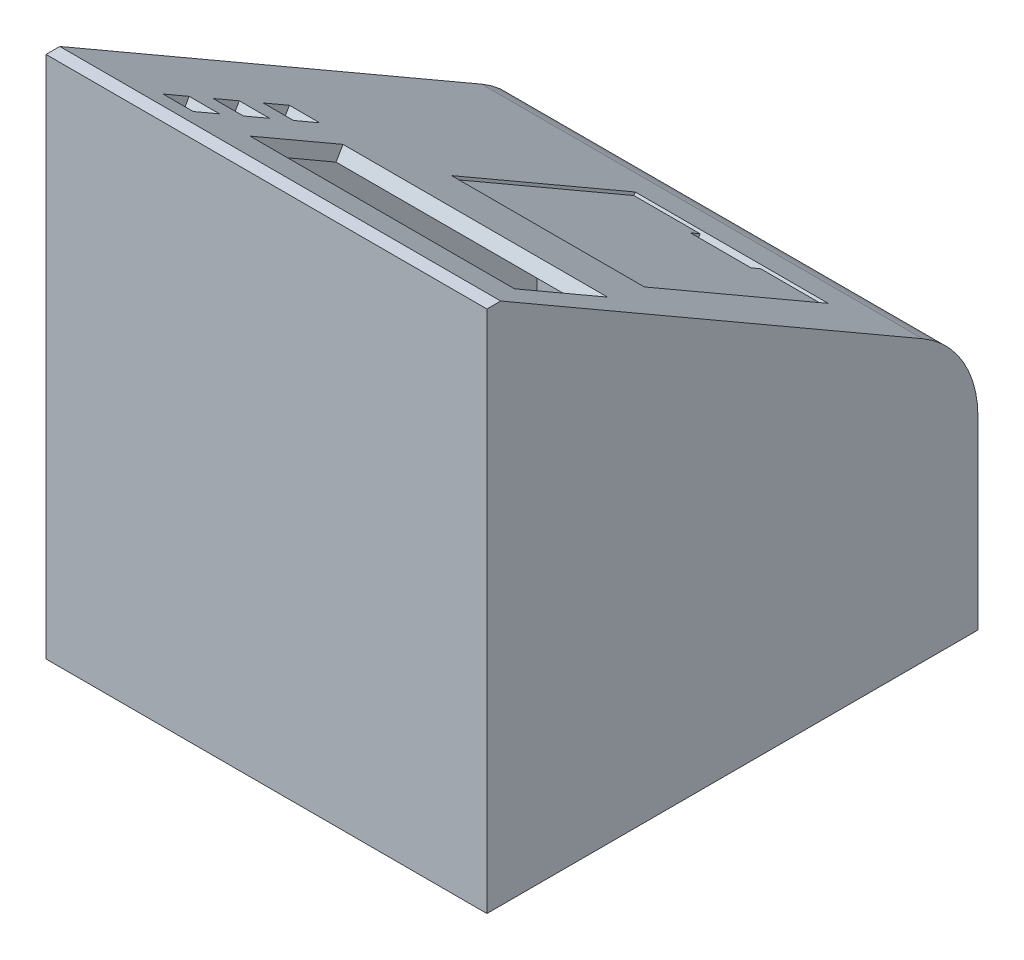
SolidWorks part; units mm, degrees
ref_plane "Front Plane" through (0, 0, 0) normal (0, 0, 1) x (1, 0, 0)
ref_plane "Top Plane" through (0, 0, 0) normal (0, 1, 0) x (1, 0, 0)
ref_plane "Right Plane" through (0, 0, 0) normal (1, 0, 0) x (0, 0, -1)
sketch "Sketch1" plane through (0, 0, 0) normal (1, 0, 0) x (0, 0, -1)
  line L0 (0, 0) -> (173.2051, -100)
  line L1 (173.2051, -100) -> (173.2051, -190)
  line L2 (173.2051, -190) -> (0, -190)
  line L3 (0, -190) -> (0, 0)
  line L4 (173.2051, -100) -> (290.6561, -100) construction
  dimension "D1" = 90
  dimension "D2" = 200
  dimension "D3" = 150
extrude "Boss-Extrude1" add sketch "Sketch1" along normal blind 5
ref_plane "Plane1" through (0, 0, 0) normal (0, 0.866, -0.5) x (1, 0, 0)
sketch "Sketch2" plane through (0, 0, 0) normal (0, 0.866, -0.5) x (1, 0, 0)
  line L0 (0, 200) -> (160, 200)
  line L1 (0, 200) -> (0, 0) construction
  line L2 (5, 200) -> (0, 200) construction
  line L3 (0, 200) -> (0, 0)
  line L4 (0, 0) -> (160, 0)
  line L5 (160, 0) -> (160, 200)
  dimension "D1" = 160
  dimension "D2" = 160
extrude "Boss-Extrude2" add sketch "Sketch2" against normal blind 5 contours L4 L5 L0 L3
ref_plane "Plane3" through (0, 0, 0) normal (0, 0, 1) x (1, 0, 0)
sketch "Sketch4" plane through (0, 0, 0) normal (0, 0, 1) x (1, 0, 0)
  line L0 (0, 0) -> (160, 0)
  line L1 (160, 0) -> (160, -190)
  line L2 (0, 0) -> (0, -190)
  line L3 (5, -190) -> (0, -190) construction
  line L4 (0, -190) -> (160, -190)
extrude "Boss-Extrude4" add sketch "Sketch4" along normal blind 5
ref_plane "Plane4" through (0, 0, -173.2051) normal (0, 0, -1) x (-1, 0, 0)
sketch "Sketch5" plane through (0, 0, -173.2051) normal (0, 0, -1) x (-1, 0, 0)
  line L0 (0, -100) -> (-160, -100)
  line L1 (-5, -100) -> (0, -100) construction
  line L2 (-160, -100) -> (-160, -190)
  line L3 (-160, -190) -> (0, -190)
  line L4 (0, -190) -> (0, -100)
extrude "Boss-Extrude5" add sketch "Sketch5" against normal blind 5
ref_plane "Plane5" through (70, 0, 0) normal (-1, 0, 0) x (0, 0, 1)
ref_plane "Plane6" through (80, 0, 0) normal (-1, 0, 0) x (0, 0, 1)
mirror "Mirror1" about plane through (80, 0, 0) normal (-1, 0, 0) of "Boss-Extrude1"
ref_plane "Plane7" through (0, 0, 0) normal (0, 0.866, -0.5) x (1, 0, 0)
sketch "Sketch6" plane through (0, 0, 0) normal (0, 0.866, -0.5) x (1, 0, 0)
  line L0 (0, 200) -> (0, 0) construction
  line L1 (160, 0) -> (0, 0) construction
  line L2 (160, 0) -> (160, 200) construction
  line L3 (160, 200) -> (0, 200) construction
  line L4 (0, 200) -> (0, 0) construction
  line L5 (160, 0) -> (0, 0) construction
  line L6 (160, 0) -> (160, 200) construction
  line L7 (160, 200) -> (0, 200) construction
  line L8 (34, 7.7765) -> (34, 64.7725) construction
  line L11 (54, 10) -> (150, 10) construction
  line L12 (150, 49) -> (150, 10) construction
  line L14 (54, 56.3152) -> (150, 56.3152)
  line L17 (28.5, 21.3152) -> (39.5, 21.3152)
  line L18 (28.5, 21.3152) -> (28.5, 10.3152)
  line L19 (28.5, 10.3152) -> (39.5, 10.3152)
  line L20 (39.5, 21.3152) -> (39.5, 10.3152)
  line L21 (28.5, 21.3152) -> (39.5, 10.3152) construction
  line L22 (28.5, 10.3152) -> (39.5, 21.3152) construction
  line L23 (28.5, 42.3152) -> (39.5, 42.3152)
  line L24 (28.5, 42.3152) -> (28.5, 31.3152)
  line L25 (28.5, 31.3152) -> (39.5, 31.3152)
  line L26 (39.5, 42.3152) -> (39.5, 31.3152)
  line L27 (28.5, 42.3152) -> (39.5, 31.3152) construction
  line L28 (28.5, 31.3152) -> (39.5, 42.3152) construction
  line L29 (28.5, 63.3152) -> (39.5, 63.3152)
  line L30 (28.5, 63.3152) -> (28.5, 52.3152)
  line L31 (28.5, 52.3152) -> (39.5, 52.3152)
  line L32 (39.5, 63.3152) -> (39.5, 52.3152)
  line L33 (28.5, 63.3152) -> (39.5, 52.3152) construction
  line L34 (28.5, 52.3152) -> (39.5, 63.3152) construction
  line L35 (54, 56.3152) -> (54, 17.3152)
  line L36 (54, 17.3152) -> (150, 17.3152)
  line L37 (150, 56.3152) -> (150, 17.3152)
  line L38 (54, 56.3152) -> (150, 17.3152) construction
  line L39 (54, 17.3152) -> (150, 56.3152) construction
  point P6 (102, 36.8152)
  point P11 (34, 15.8152)
  point P17 (34, 36.8152)
  point P22 (34, 57.8152)
  point P27 (0, 0)
  dimension "D2" = 96
  dimension "D3" = 10
  dimension "D4" = 10
  dimension "D5" = 39
  dimension "D6" = 11
  dimension "D7" = 11
  dimension "D8" = 11
  dimension "D9" = 11
  dimension "D10" = 10
  dimension "D11" = 10
extrude "Cut-Extrude2" cut sketch "Sketch6" against normal blind 5
fillet "Fillet1" radius 40 1 edges at (80, -100, -173.2051)
sketch "Sketch7" plane through (0, 0, 0) normal (0, 0.866, -0.5) x (1, 0, 0)
  line L0 (34, 63.3152) -> (160, 63.3152) construction
  line L1 (39.5, 63.3152) -> (28.5, 63.3152) construction
  line L2 (160, 0) -> (160, 176.906) construction
  line L4 (70, 160.3152) -> (140, 160.3152)
  line L5 (70, 160.3152) -> (70, 83.3152)
  line L6 (70, 83.3152) -> (140, 83.3152)
  line L7 (140, 160.3152) -> (140, 83.3152)
  line L8 (70, 160.3152) -> (140, 83.3152) construction
  line L9 (70, 83.3152) -> (140, 160.3152) construction
  point P6 (105, 121.8152)
  dimension "D1" = 70
  dimension "D2" = 77
  dimension "D3" = 20
  dimension "D4" = 20
extrude "Cut-Extrude3" cut sketch "Sketch7" against normal blind 1
sketch "Sketch8" plane through (0, -0.866, 0.5) normal (0, 0.866, -0.5) x (1, 0, 0)
  line L1 (140, 160.3152) -> (70, 160.3152) construction
  line L2 (94, 160.3152) -> (116, 160.3152)
  line L3 (94, 160.3152) -> (94, 156.3152)
  line L4 (94, 156.3152) -> (116, 156.3152)
  line L5 (116, 160.3152) -> (116, 156.3152)
  line L6 (94, 160.3152) -> (116, 156.3152) construction
  line L7 (94, 156.3152) -> (116, 160.3152) construction
  line L9 (70, 160.3152) -> (70, 83.3152) construction
  point P4 (105, 158.3152)
  point P9 (105, 160.3152)
  point P12 (0, 0)
  dimension "D1" = 22
  dimension "D2" = 4
  dimension "D3" = 0
  dimension "D4" = 35
extrude "Cut-Extrude4" cut sketch "Sketch8" against normal blind 4
sketch "Sketch9" plane through (0, 0, 0) normal (0, 0.866, -0.5) x (1, 0, 0)
  line L0 (160, 176.906) -> (0, 176.906) construction
  line L1 (0, 176.906) -> (0, 0) construction
  line L2 (160, 176.906) -> (0, 176.906) construction
  line L3 (0, 176.906) -> (0, 0) construction
  line L5 (15, 151.8152) -> (55, 151.8152)
  line L6 (15, 151.8152) -> (15, 91.8152)
  line L7 (15, 91.8152) -> (55, 91.8152)
  line L8 (55, 151.8152) -> (55, 91.8152)
  line L9 (15, 151.8152) -> (55, 91.8152) construction
  line L10 (15, 91.8152) -> (55, 151.8152) construction
  line L12 (70, 83.3152) -> (11.8162, 83.3152) construction
  point P2 (35, 121.8152)
  dimension "D1" = 40
  dimension "D2" = 60
  dimension "D3" = 15
  dimension "D4" = 8.5
extrude "Cut-Extrude5" cut sketch "Sketch9" against normal blind 5
sketch "Sketch12" plane through (0, 0, 0) normal (0, 0.866, -0.5) x (1, 0, 0)
  line L0 (55, 91.8152) -> (55, 151.8152) construction
  line L1 (15, 91.8152) -> (55, 91.8152) construction
  line L2 (15, 151.8152) -> (15, 91.8152) construction
  line L3 (55, 151.8152) -> (15, 151.8152) construction
  line L4 (55, 91.8152) -> (55, 151.8152)
  line L5 (15, 91.8152) -> (55, 91.8152)
  line L6 (15, 151.8152) -> (15, 91.8152)
  line L7 (55, 151.8152) -> (15, 151.8152)
extrude "Boss-Extrude6" add sketch "Sketch12" against normal blind 2
ref_plane "Plane8" through (0, 0, -173.2051) normal (0, 0, -1) x (-1, 0, 0)
sketch "Sketch14" plane through (0, 0, -173.2051) normal (0, 0, -1) x (-1, 0, 0)
  line L0 (0, -123.094) -> (-160, -123.094) construction
  line L1 (-140, -130.094) -> (-63, -130.094)
  line L2 (-140, -130.094) -> (-140, -183.094)
  line L3 (-140, -183.094) -> (-63, -183.094)
  line L4 (-63, -130.094) -> (-63, -183.094)
  line L5 (-140, -130.094) -> (-63, -183.094) construction
  line L6 (-140, -183.094) -> (-63, -130.094) construction
  line L7 (0, -123.094) -> (-160, -123.094) construction
  line L8 (-160, -190) -> (0, -190) construction
  line L9 (-160, -190) -> (0, -190) construction
  line L10 (0, -190) -> (0, -123.094) construction
  line L11 (0, -190) -> (0, -123.094) construction
  line L12 (-160, -123.094) -> (-160, -190) construction
  point P0 (-101.5, -156.594)
  dimension "D1" = 77
  dimension "D2" = 53
  dimension "D3" = 20
  dimension "D4" = 7
extrude "Cut-Extrude6" cut sketch "Sketch14" against normal blind 5
sketch "Sketch15" plane through (0, 0, -173.2051) normal (0, 0, -1) x (-1, 0, 0)
  line L0 (-63, -130.094) -> (-31.075, -130.094) construction
  line L1 (-63, -142.094) -> (-31.075, -142.094) construction
  line L2 (-63, -183.094) -> (-63, -130.094) construction
  line L3 (-63, -183.094) -> (-31.075, -183.094) construction
  line L4 (-63, -171.094) -> (-31.075, -171.094) construction
  line L5 (-63, -142.094) -> (-60, -142.094)
  line L6 (-60, -142.094) -> (-60, -171.094)
  line L7 (-60, -171.094) -> (-63, -171.094)
  line L8 (-63, -171.094) -> (-63, -142.094)
  line L15 (-140, -171.094) -> (-140, -142.094)
  line L16 (-143, -142.094) -> (-143, -171.094)
  line L17 (-143, -171.094) -> (-140, -171.094)
  line L18 (-140, -142.094) -> (-143, -142.094)
  dimension "D1" = 12
  dimension "D2" = 12
  dimension "D3" = 3
extrude "Cut-Extrude7" cut sketch "Sketch15" against normal blind 5
ref_plane "Plane9" through (0, -4.3301, 2.5) normal (0, -0.866, 0.5) x (-1, 0, 0)
sketch "Sketch17" plane through (0, -4.3301, 2.5) normal (0, -0.866, 0.5) x (-1, 0, 0)
  line L0 (-160, 0) -> (-160, 176.906) construction
  line L1 (-53, 66.7395) -> (-151, 66.7395) construction
  line L2 (-53, 66.7395) -> (-53, 6.7395) construction
  line L3 (-53, 6.7395) -> (-151, 6.7395) construction
  line L4 (-151, 66.7395) -> (-151, 6.7395) construction
  line L5 (-53, 66.7395) -> (-151, 6.7395) construction
  line L6 (-53, 6.7395) -> (-151, 66.7395) construction
  circle A0 centre (-54.75, 64.9895) radius 1.75
  circle A2 centre (-149.25, 64.9895) radius 1.75
  circle A3 centre (-54.75, 8.4895) radius 1.75
  circle A4 centre (-149.25, 8.4895) radius 1.75
  point P0 (-102, 36.7395)
  dimension "D6" = 3.5
  dimension "D1" = 98
  dimension "D2" = 60
  dimension "D3" = 9
  dimension "D4" = 1.75
  dimension "D5" = 1.75
extrude "Cut-Extrude9" cut sketch "Sketch17" against normal blind 4
ref_plane "Plane10" through (0, -1.7321, 1) normal (0, -0.866, 0.5) x (-1, 0, 0)
sketch "Sketch21" plane through (0, -1.7321, 1) normal (0, -0.866, 0.5) x (-1, 0, 0)
  line L0 (-55, 91.8152) -> (-55, 151.8152) construction
  line L1 (-15, 151.8152) -> (-15, 91.8152) construction
  line L2 (-55, 151.8152) -> (-15, 151.8152) construction
  line L3 (-55, 91.8152) -> (-55, 151.8152) construction
  line L4 (-15, 151.8152) -> (-15, 91.8152) construction
  line L5 (-55, 151.8152) -> (-15, 151.8152) construction
  line L6 (-55, 91.8152) -> (-15, 91.8152) construction
  circle A0 centre (-48.5, 98.3152) radius 1.5
  circle A1 centre (-21.5, 97.3152) radius 1.5
  circle A2 centre (-17.5, 136.3152) radius 1.5
  circle A4 centre (-52.5, 136.3152) radius 1.5
  dimension "D1" = 3
  dimension "D4" = 3
  dimension "D7" = 3
  dimension "D2" = 6.5
  dimension "D3" = 6.5
  dimension "D5" = 6.5
  dimension "D6" = 5.5
  dimension "D8" = 2.5
  dimension "D9" = 15.5
extrude "Boss-Extrude8" add sketch "Sketch21" along normal blind 4
ref_plane "Plane11" through (0, -190, 0) normal (0, -1, 0) x (-1, 0, 0)
sketch "Sketch23" plane through (0, -190, 0) normal (0, -1, 0) x (-1, 0, 0)
  line L0 (-155, 0) -> (-148.5035, 7.6023) construction
  line L1 (-155, 0) -> (-145, 0)
  line L2 (-155, 0) -> (-155, 10)
  arc A0 (-145, 0) -> (-155, 10) centre (-155, 0) ccw
  circle A1 centre (-151.7517, 3.8012) radius 1.5
  dimension "D1" = 3
  dimension "D2" = 20
extrude "Boss-Extrude9" add sketch "Sketch23" against normal blind 10
mirror "Mirror2" about plane through (80, 0, 0) normal (-1, 0, 0) of "Boss-Extrude9"
sketch "Sketch25" plane through (0, -190, 0) normal (0, -1, 0) x (-1, 0, 0)
  line L0 (-155, 168.2051) -> (-148.2405, 160.8356) construction
  line L1 (-155, 168.2051) -> (-145, 168.2051)
  line L2 (-155, 168.2051) -> (-155, 158.2051)
  arc A0 (-155, 158.2051) -> (-145, 168.2051) centre (-155, 168.2051) ccw
  circle A1 centre (-151.6203, 164.5203) radius 1.5
  dimension "D1" = 20
  dimension "D2" = 3
extrude "Boss-Extrude10" add sketch "Sketch25" against normal blind 10
mirror "Mirror4" about plane through (80, 0, 0) normal (-1, 0, 0) of "Boss-Extrude10"
